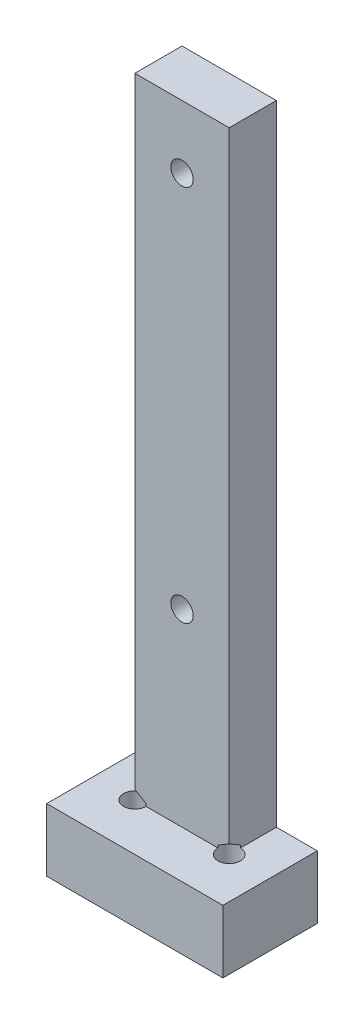
SolidWorks part; units mm, degrees
ref_plane "Front Plane" through (0, 0, 0) normal (0, 0, 1) x (1, 0, 0)
ref_plane "Top Plane" through (0, 0, 0) normal (0, 1, 0) x (1, 0, 0)
ref_plane "Right Plane" through (0, 0, 0) normal (1, 0, 0) x (0, 0, -1)
sketch "Sketch1" plane through (0, 0, 0) normal (0, 1, 0) x (1, 0, 0)
  line L1 (-8.89, -4.7625) -> (8.89, -4.7625)
  line L2 (-8.89, -4.7625) -> (-8.89, 4.7625)
  line L3 (-8.89, 4.7625) -> (8.89, 4.7625)
  line L4 (8.89, -4.7625) -> (8.89, 4.7625)
  line L5 (-8.89, -4.7625) -> (8.89, 4.7625) construction
  line L6 (-8.89, 4.7625) -> (8.89, -4.7625) construction
  point P0 (0, 0)
  dimension "D1" = 9.525
  dimension "D2" = 17.78
extrude "Boss-Extrude1" add sketch "Sketch1" along normal blind 69.85
sketch "Sketch2" plane through (0, 69.85, 0) normal (0, 1, 0) x (1, 0, 0)
  line L0 (8.89, -4.7625) -> (8.89, 4.7625) construction
  line L1 (-8.89, -4.7625) -> (8.89, -4.7625)
  line L2 (-8.89, -4.7625) -> (-8.89, 0)
  line L3 (-8.89, 0) -> (8.89, 0)
  line L4 (8.89, -4.7625) -> (8.89, 0)
  line L5 (8.89, 4.7625) -> (-8.89, 4.7625) construction
  dimension "D1" = 4.7625
extrude "Cut-Extrude1" cut sketch "Sketch2" against normal offset from surface (63.5 mm away) 6.35 up to face at (0, 0, 0)
hole_wizard "#4-40 Tapped Hole1" positions "Sketch4" profile "Sketch5" tap size "#4-40" standard "ANSI Inch"
sketch "Sketch4" plane through (0, 0, 0) normal (0, -1, 0) x (-1, 0, 0)
  line L4 (-4.7625, 0) -> (4.7625, 0) construction
  point P0 (-4.7625, 0)
  point P2 (4.7625, 0)
  dimension "D1" = 9.525
sketch "Sketch5" plane through (4.7625, 0, 0) normal (1, 0, 0) x (0, 0, -1)
  line L0 (0, 0) -> (0, 7.2832)
  line L1 (0, 7.2832) -> (1.1303, 6.604)
  line L2 (1.1303, 6.604) -> (1.1303, 0)
  line L5 (1.1303, 0) -> (0, 0)
  line L10 (0, 7.2832) -> (-1.1303, 6.604) construction
  line L11 (0, -6.35) -> (0, 107.95) construction
  dimension "Tap Drill Dia." = 2.2606
  dimension "Tap Drill Depth" = 6.604
  dimension "Drill Angle" = 118
cosmetic thread "Hole Thread1" parameters "D1"=5.588, "D2"=2.8448
cosmetic thread "Hole Thread2" parameters "D1"=5.588, "D2"=2.8448
hole_wizard "#4-40 Tapped Hole2" positions "Sketch7" profile "Sketch8" tap size "#4-40" standard "ANSI Inch"
sketch "Sketch7" plane through (0, 0, 0) normal (0, 0, 1) x (1, 0, 0)
  line L0 (8.89, 69.85) -> (-8.89, 69.85) construction
  point P0 (0, 25.4)
  point P2 (0, 63.5)
  point P5 (0, 0)
  point P7 (0, 68.0353)
  dimension "D1" = 38.1
  dimension "D2" = 6.35
sketch "Sketch8" plane through (0, 25.4, 0) normal (1, 0, 0) x (0, -1, 0)
  line L0 (0, 0) -> (0, 9.5692)
  line L1 (0, 9.5692) -> (1.1303, 8.89)
  line L2 (1.1303, 8.89) -> (1.1303, 0)
  line L5 (1.1303, 0) -> (0, 0)
  line L10 (0, 9.5692) -> (-1.1303, 8.89) construction
  line L11 (0, -6.35) -> (0, 107.95) construction
  dimension "Tap Drill Dia." = 2.2606
  dimension "Tap Drill Depth" = 8.89
  dimension "Drill Angle" = 118
cosmetic thread "Hole Thread3" parameters "D1"=5.588, "D2"=2.8448
cosmetic thread "Hole Thread4" parameters "D1"=5.588, "D2"=2.8448
sketch "Sketch9" plane through (0, 0, 0) normal (0, 0, 1) x (1, 0, 0)
  line L0 (-8.89, 6.35) -> (8.89, 6.35) construction
  line L1 (-8.89, 69.85) -> (-4.7625, 69.85)
  line L2 (-8.89, 69.85) -> (-8.89, 6.35)
  line L3 (-8.89, 6.35) -> (-4.7625, 6.35)
  line L4 (-4.7625, 69.85) -> (-4.7625, 6.35)
  line L5 (3.6322, 6.35) -> (-3.6322, 6.35) construction
  line L6 (8.89, 69.85) -> (4.7625, 69.85)
  line L7 (8.89, 69.85) -> (8.89, 6.35)
  line L8 (8.89, 6.35) -> (4.7625, 6.35)
  line L9 (4.7625, 69.85) -> (4.7625, 6.35)
  dimension "D1" = 9.525
extrude "Cut-Extrude2" cut sketch "Sketch9" against normal through all
